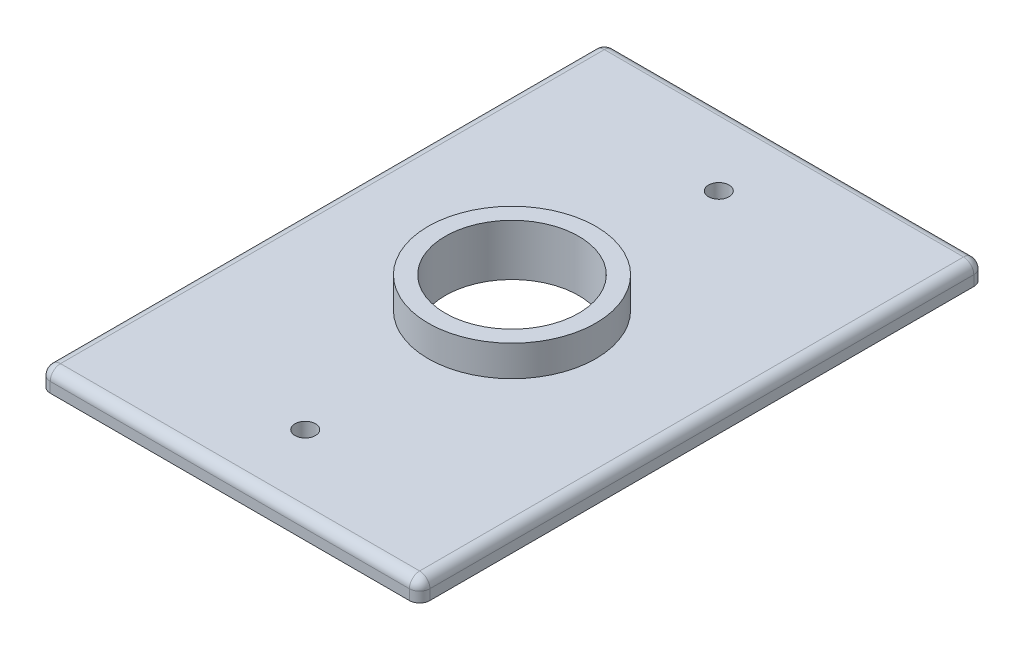
SolidWorks part; units mm, degrees
ref_plane "Plano frontal" through (0, 0, 0) normal (0, 0, 1) x (1, 0, 0)
ref_plane "Plano superior" through (0, 0, 0) normal (0, 1, 0) x (1, 0, 0)
ref_plane "Plano direito" through (0, 0, 0) normal (1, 0, 0) x (0, 0, -1)
sketch "Esboço1" plane through (0, 0, 0) normal (0, 1, 0) x (1, 0, 0)
  line L0 (0, 0) -> (0, 10.9711) construction
  line L1 (0, 10.9711) -> (0, 0) construction
  line L2 (0, 0) -> (0, -11.4474) construction
  line L4 (-9.2925, 10.9711) -> (64.7075, 10.9711)
  line L5 (-9.2925, 10.9711) -> (-9.2925, -99.0289)
  line L6 (-9.2925, -99.0289) -> (64.7075, -99.0289)
  line L7 (64.7075, 10.9711) -> (64.7075, -99.0289)
  dimension "D1" = 74
  dimension "D2" = 110
extrude "Ressalto-extrusão1" add sketch "Esboço1" along normal blind 4
fillet "Filete1" radius 2 1 edges at (27.7075, 4, 99.0289)
fillet "Filete2" radius 2 3 edges at (64.7075, 1, 99.0289) (64.7075, 3.4142, 98.4431) (64.7075, 4, 43.0289)
fillet "Filete3" radius 2 3 edges at (64.7075, 1, -10.9711) (64.1217, 3.4142, -10.9711) (26.7075, 4, -10.9711)
fillet "Filete4" radius 2 5 edges at (-9.2925, 1, -10.9711) (-9.2925, 3.4142, -10.3853) (-9.2925, 1, 99.0289) (-9.2925, 3.4142, 98.4431) (-9.2925, 4, 44.0289)
sketch "Esboço2" plane through (0, 0, 0) normal (0, 1, 0) x (1, 0, 0)
  line L0 (-7.2925, 8.9711) -> (62.7075, -97.0289) construction
  line L1 (62.7075, -97.0289) -> (62.7075, 8.9711) construction
  line L2 (62.7075, 8.9711) -> (-7.2925, -97.0289) construction
  circle A0 centre (27.7075, -44.0289) radius 13
  dimension "D1" = 26
extrude "Corte-extrusão1" cut sketch "Esboço2" along normal blind 15 and the other way blind 10
sketch "Esboço3" plane through (0, 0, 0) normal (0, 1, 0) x (1, 0, 0)
  line L0 (27.7075, -99.0289) -> (27.7075, 10.9711) construction
  line L1 (-7.2925, -99.0289) -> (62.7075, -99.0289) construction
  line L2 (62.7075, 10.9711) -> (-7.2925, 10.9711) construction
  line L3 (-9.2925, -44.0289) -> (64.7075, -44.0289) construction
  line L4 (-9.2925, 8.9711) -> (-9.2925, -97.0289) construction
  line L5 (64.7075, -97.0289) -> (64.7075, 8.9711) construction
  circle A0 centre (27.7075, -84.3289) radius 2
  circle A1 centre (27.7075, -3.7289) radius 2
  dimension "D3" = 4
  dimension "D4" = 4
  dimension "D1" = 40.3
  dimension "D2" = 40.3
extrude "Corte-extrusão3" cut sketch "Esboço3" against normal blind 15 and the other way blind 15
sketch "Esboço4" plane through (0, 0, 0) normal (0, 1, 0) x (1, 0, 0)
  circle A0 centre (27.7075, -44.0289) radius 16.3437
  circle A1 centre (27.7075, -44.0289) radius 13
extrude "Ressalto-extrusão2" add sketch "Esboço4" along normal blind 10
